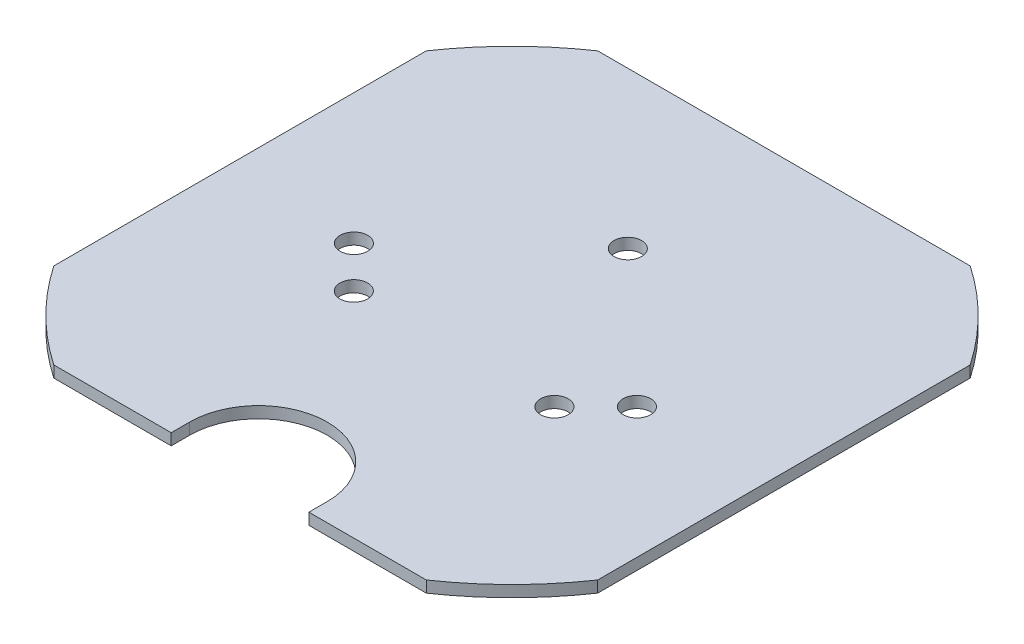
SolidWorks part; units mm, degrees
material "A-Glass Fiber"
ref_plane "Top Plane" through (0, 0, 0) normal (0, 0, 1) x (1, 0, 0)
ref_plane "Front Plane" through (0, 0, 0) normal (0, 1, 0) x (1, 0, 0)
ref_plane "Right Plane" through (0, 0, 0) normal (1, 0, 0) x (0, 0, -1)
sketch "Sketch1" plane through (0, 0, 0) normal (0, 1, 0) x (1, 0, 0)
  line L0 (0, 15.9552) -> (0, -37.465) construction
  line L1 (-25.6581, 37.465) -> (25.6581, 37.465)
  line L2 (-37.465, 25.6581) -> (-37.465, -25.6581)
  line L3 (-25.6581, -37.465) -> (-9.4805, -37.465)
  line L4 (37.465, 25.6581) -> (37.465, -25.6581)
  line L5 (0, 0) -> (13.8176, -7.9776) construction
  line L6 (-9.4805, -37.465) -> (-9.4805, -34.925)
  line L7 (9.4805, -37.465) -> (25.6581, -37.465)
  line L8 (25.6581, -37.465) -> (-25.6581, -37.465) construction
  line L9 (37.465, 0) -> (-37.465, 0) construction
  line L10 (9.4805, -37.465) -> (9.4805, -34.925)
  line L11 (-13.8176, -7.9776) -> (0, 0) construction
  line L12 (-19.4945, -2.286) -> (19.4945, -2.286) construction
  arc A0 (-37.465, -25.6581) -> (-25.6581, -37.465) centre (0, 0) ccw
  arc A1 (37.465, 25.6581) -> (25.6581, 37.465) centre (0, 0) ccw
  arc A2 (-25.6581, 37.465) -> (-37.465, 25.6581) centre (0, 0) ccw
  arc A3 (25.6581, -37.465) -> (37.465, -25.6581) centre (0, 0) ccw
  circle A4 centre (0, 0) radius 45.4089 construction
  arc A5 (-9.4805, -34.925) -> (9.4805, -34.925) centre (0, -34.925) cw
  circle A6 centre (0, 0) radius 15.9552 construction
  circle A7 centre (13.8176, -7.9776) radius 1.905
  circle A8 centre (0, 15.9552) radius 1.905
  circle A9 centre (-13.8176, -7.9776) radius 1.905
  circle A10 centre (-19.4945, -2.286) radius 1.905
  circle A11 centre (19.4945, -2.286) radius 1.905
  point P0 (0, 0)
  point P32 (0, -2.286)
  dimension "D2" = 90.8177
  dimension "D3" = 74.93
  dimension "D4" = 2.54
  dimension "D1" = 3.81
  dimension "D7" = 2.286
  dimension "D9" = 27.6352
  dimension "D10" = 9.4805
  dimension "D5" = 120
  dimension "D6" = 120
  dimension "D8" = 19.4945
extrude "Boss-Extrude1" add sketch "Sketch1" along normal blind 1.5748
sketch "Sketch2" plane through (0, 0, 0) normal (0, -1, 0) x (1, 0, 0)
  line L0 (0, 27.9844) -> (0, -37.465) construction
  line L1 (25.6581, -37.465) -> (-25.6581, -37.465) construction
  line L2 (-1.6129, 22.225) -> (1.6129, 22.225) construction
  line L4 (-2.8829, 23.495) -> (-0.3429, 23.495)
  line L5 (-2.8829, 23.495) -> (-2.8829, 20.955)
  line L6 (-2.8829, 20.955) -> (-0.3429, 20.955)
  line L7 (-0.3429, 23.495) -> (-0.3429, 20.955)
  line L8 (-2.8829, 23.495) -> (-0.3429, 20.955) construction
  line L9 (-2.8829, 20.955) -> (-0.3429, 23.495) construction
  line L10 (0.3429, 23.495) -> (2.8829, 23.495)
  line L11 (0.3429, 23.495) -> (0.3429, 20.955)
  line L12 (0.3429, 20.955) -> (2.8829, 20.955)
  line L13 (2.8829, 23.495) -> (2.8829, 20.955)
  line L14 (0.3429, 23.495) -> (2.8829, 20.955) construction
  line L15 (0.3429, 20.955) -> (2.8829, 23.495) construction
  line L16 (9.4805, 37.465) -> (25.6581, 37.465) construction
  line L17 (-25.6581, 37.465) -> (-9.4805, 37.465) construction
  line L32 (6.25, -30.5277) -> (5.25, -30.5277)
  line L33 (6.25, -30.5277) -> (6.25, -32.0277)
  line L34 (6.25, -32.0277) -> (5.25, -32.0277)
  line L35 (5.25, -30.5277) -> (5.25, -32.0277)
  line L37 (6.25, -30.5277) -> (5.25, -32.0277) construction
  line L39 (6.25, -32.0277) -> (5.25, -30.5277) construction
  line L53 (32.0277, -19.75) -> (30.5277, -19.75)
  line L55 (5.75, -31.2777) -> (0, -31.2777) construction
  line L56 (32.0277, -19.75) -> (32.0277, -18.75)
  line L57 (32.0277, -18.75) -> (30.5277, -18.75)
  line L58 (30.5277, -19.75) -> (30.5277, -18.75)
  line L59 (32.0277, -19.75) -> (30.5277, -18.75) construction
  line L60 (32.0277, -18.75) -> (30.5277, -19.75) construction
  line L61 (29.8277, -5.25) -> (28.3277, -5.25)
  line L62 (29.8277, -5.25) -> (29.8277, -6.25)
  line L63 (29.8277, -6.25) -> (28.3277, -6.25)
  line L64 (28.3277, -5.25) -> (28.3277, -6.25)
  line L65 (29.8277, -5.25) -> (28.3277, -6.25) construction
  line L75 (31.2777, -19.25) -> (0, -19.25) construction
  line L76 (-17.1669, 34.3496) -> (-17.874, 35.0567)
  line L77 (32.0277, 6.25) -> (30.5277, 6.25)
  line L78 (0, 35.8354) -> (0, 27.9844) construction
  line L79 (29.8277, -6.25) -> (28.3277, -5.25) construction
  line L80 (6.25, 1.85) -> (7.25, 1.85)
  line L81 (6.25, 1.85) -> (6.25, 0.35)
  line L82 (6.25, 0.35) -> (7.25, 0.35)
  line L83 (7.25, 1.85) -> (7.25, 0.35)
  line L84 (6.25, 1.85) -> (7.25, 0.35) construction
  line L85 (6.25, 0.35) -> (7.25, 1.85) construction
  line L86 (-6.25, -0.35) -> (-7.25, -0.35)
  line L87 (-6.25, -0.35) -> (-6.25, -1.85)
  line L88 (-6.25, -1.85) -> (-7.25, -1.85)
  line L89 (-7.25, -0.35) -> (-7.25, -1.85)
  line L90 (-6.25, -0.35) -> (-7.25, -1.85) construction
  line L91 (-6.25, -1.85) -> (-7.25, -0.35) construction
  line L92 (-28.3277, -18.75) -> (-29.8277, -18.75)
  line L93 (-28.3277, -18.75) -> (-28.3277, -19.75)
  line L94 (-28.3277, -19.75) -> (-29.8277, -19.75)
  line L95 (-29.8277, -18.75) -> (-29.8277, -19.75)
  line L96 (-28.3277, -18.75) -> (-29.8277, -19.75) construction
  line L97 (-28.3277, -19.75) -> (-29.8277, -18.75) construction
  line L98 (-30.5277, -5.25) -> (-32.0277, -5.25)
  line L99 (-30.5277, -5.25) -> (-30.5277, -6.25)
  line L100 (-30.5277, -6.25) -> (-32.0277, -6.25)
  line L101 (-32.0277, -5.25) -> (-32.0277, -6.25)
  line L102 (-30.5277, -5.25) -> (-32.0277, -6.25) construction
  line L103 (-30.5277, -6.25) -> (-32.0277, -5.25) construction
  line L104 (32.0277, 6.25) -> (32.0277, 5.25)
  line L105 (32.0277, 5.25) -> (30.5277, 5.25)
  line L106 (30.5277, 6.25) -> (30.5277, 5.25)
  line L107 (32.0277, 6.25) -> (30.5277, 5.25) construction
  line L108 (32.0277, 5.25) -> (30.5277, 6.25) construction
  line L109 (29.8277, 19.75) -> (28.3277, 19.75)
  line L110 (29.8277, 19.75) -> (29.8277, 18.75)
  line L111 (29.8277, 18.75) -> (28.3277, 18.75)
  line L112 (28.3277, 19.75) -> (28.3277, 18.75)
  line L113 (29.8277, 19.75) -> (28.3277, 18.75) construction
  line L114 (29.8277, 18.75) -> (28.3277, 19.75) construction
  line L115 (-28.3277, 6.25) -> (-29.8277, 6.25)
  line L116 (-28.3277, 6.25) -> (-28.3277, 5.25)
  line L117 (-28.3277, 5.25) -> (-29.8277, 5.25)
  line L118 (-29.8277, 6.25) -> (-29.8277, 5.25)
  line L119 (-28.3277, 6.25) -> (-29.8277, 5.25) construction
  line L120 (-28.3277, 5.25) -> (-29.8277, 6.25) construction
  line L121 (19.75, -28.3277) -> (18.75, -28.3277)
  line L122 (19.75, -28.3277) -> (19.75, -29.8277)
  line L123 (19.75, -29.8277) -> (18.75, -29.8277)
  line L124 (18.75, -28.3277) -> (18.75, -29.8277)
  line L125 (19.75, -28.3277) -> (18.75, -29.8277) construction
  line L126 (19.75, -29.8277) -> (18.75, -28.3277) construction
  line L127 (-5.25, -28.3277) -> (-6.25, -28.3277)
  line L128 (-5.25, -28.3277) -> (-5.25, -29.8277)
  line L129 (-5.25, -29.8277) -> (-6.25, -29.8277)
  line L130 (-6.25, -28.3277) -> (-6.25, -29.8277)
  line L131 (-5.25, -28.3277) -> (-6.25, -29.8277) construction
  line L132 (-5.25, -29.8277) -> (-6.25, -28.3277) construction
  line L133 (-18.75, -30.5277) -> (-19.75, -30.5277)
  line L134 (-18.75, -30.5277) -> (-18.75, -32.0277)
  line L135 (-18.75, -32.0277) -> (-19.75, -32.0277)
  line L136 (-19.75, -30.5277) -> (-19.75, -32.0277)
  line L137 (-18.75, -30.5277) -> (-19.75, -32.0277) construction
  line L138 (-18.75, -32.0277) -> (-19.75, -30.5277) construction
  line L139 (-5.75, -29.0777) -> (0, -29.0777) construction
  line L140 (-19.25, -31.2777) -> (0, -31.2777) construction
  line L141 (19.25, -29.0777) -> (0, -29.0777) construction
  line L142 (-30.5277, 19.75) -> (-32.0277, 19.75)
  line L143 (-30.5277, 19.75) -> (-30.5277, 18.75)
  line L144 (-30.5277, 18.75) -> (-32.0277, 18.75)
  line L145 (-32.0277, 19.75) -> (-32.0277, 18.75)
  line L146 (-30.5277, 19.75) -> (-32.0277, 18.75) construction
  line L147 (-30.5277, 18.75) -> (-32.0277, 19.75) construction
  line L148 (16.6719, 34.8446) -> (15.6113, 35.9052)
  line L149 (16.6719, 34.8446) -> (17.379, 35.5517)
  line L150 (17.379, 35.5517) -> (16.3184, 36.6123)
  line L151 (15.6113, 35.9052) -> (16.3184, 36.6123)
  line L152 (16.6719, 34.8446) -> (16.3184, 36.6123) construction
  line L153 (17.379, 35.5517) -> (15.6113, 35.9052) construction
  line L154 (9.3887, 24.4501) -> (8.3281, 25.5108)
  line L155 (9.3887, 24.4501) -> (8.6816, 23.743)
  line L156 (8.6816, 23.743) -> (7.621, 24.8037)
  line L157 (8.3281, 25.5108) -> (7.621, 24.8037)
  line L158 (9.3887, 24.4501) -> (7.621, 24.8037) construction
  line L159 (8.6816, 23.743) -> (8.3281, 25.5108) construction
  line L160 (-6.0653, 26.3593) -> (-6.7724, 27.0664)
  line L161 (-6.0653, 26.3593) -> (-7.126, 25.2986)
  line L162 (-7.126, 25.2986) -> (-7.8331, 26.0057)
  line L163 (-6.7724, 27.0664) -> (-7.8331, 26.0057)
  line L164 (-6.0653, 26.3593) -> (-7.8331, 26.0057) construction
  line L165 (-7.126, 25.2986) -> (-6.7724, 27.0664) construction
  line L166 (-17.1669, 34.3496) -> (-18.2276, 33.2889)
  line L167 (-18.2276, 33.2889) -> (-18.9347, 33.996)
  line L168 (-17.874, 35.0567) -> (-18.9347, 33.996)
  line L169 (-17.1669, 34.3496) -> (-18.9347, 33.996) construction
  line L170 (-18.2276, 33.2889) -> (-17.874, 35.0567) construction
  line L171 (-29.0777, -19.25) -> (0, -19.25) construction
  line L172 (29.0777, -5.75) -> (0, -5.75) construction
  line L173 (-31.2777, -5.75) -> (0, -5.75) construction
  line L174 (31.2777, 5.75) -> (0, 5.75) construction
  line L175 (-29.0777, 5.75) -> (0, 5.75) construction
  line L176 (29.0777, 19.25) -> (0, 19.25) construction
  line L177 (-31.2777, 19.25) -> (0, 19.25) construction
  line L178 (6.75, 1.1) -> (0, 1.1) construction
  line L179 (-6.75, -1.1) -> (0, -1.1) construction
  circle A1 centre (-13.8176, 7.9776) radius 2.921
  circle A2 centre (-19.4945, 2.286) radius 2.921
  circle A3 centre (0, -15.9552) radius 2.921
  circle A4 centre (19.4945, 2.286) radius 2.921
  circle A5 centre (13.8176, 7.9776) radius 2.921
  circle A6 centre (-13.8176, 7.9776) radius 1.905 construction
  arc A7 (-9.4805, 34.925) -> (9.4805, 34.925) centre (0, 34.925) ccw construction
  point P47 (5.75, -31.2777)
  point P78 (19.25, -29.0777)
  point P86 (-5.75, -29.0777)
  point P91 (-19.25, -31.2777)
  point P110 (31.2777, -19.25)
  point P115 (29.0777, -5.75)
  point P120 (6.75, 1.1)
  point P125 (-6.75, -1.1)
  point P130 (-29.0777, -19.25)
  point P135 (-31.2777, -5.75)
  point P157 (31.2777, 5.75)
  point P162 (29.0777, 19.25)
  point P167 (-29.0777, 5.75)
  point P172 (-31.2777, 19.25)
  point P178 (16.4952, 35.7285)
  point P183 (8.5048, 24.6269)
  point P188 (-6.9492, 26.1825)
  point P193 (-18.0508, 34.1728)
  dimension "D4" = 1.016
  dimension "D43" = 12.7
  dimension "D1" = 2.54
  dimension "D3" = 1.6129
  dimension "D5" = 45
  dimension "D6" = 45
  dimension "D7" = 45
  dimension "D8" = 45
  dimension "D9" = 31.2777
  dimension "D10" = 29.0777
  dimension "D11" = 29.0777
  dimension "D12" = 31.2777
  dimension "D13" = 5.75
  dimension "D14" = 5.75
  dimension "D15" = 6.1873
  dimension "D16" = 19.25
  dimension "D17" = 19.25
  dimension "D18" = 1.5
  dimension "D19" = 1
  dimension "D20" = 8.3873
  dimension "D21" = 6.1873
  dimension "D22" = 8.3873
  dimension "D23" = 18.215
  dimension "D24" = 31.715
  dimension "D25" = 6.75
  dimension "D26" = 6.75
  dimension "D27" = 38.565
  dimension "D28" = 36.365
  dimension "D29" = 43.215
  dimension "D30" = 56.715
  dimension "D31" = 31.2777
  dimension "D32" = 29.0777
  dimension "D33" = 29.0777
  dimension "D34" = 31.2777
  dimension "D35" = 16.4952
  dimension "D36" = 1.7365
  dimension "D37" = 8.5048
  dimension "D38" = 12.8381
  dimension "D39" = 11.2825
  dimension "D40" = 6.9492
  dimension "D41" = 18.0508
  dimension "D42" = 3.2922
split line "Split Line1"
